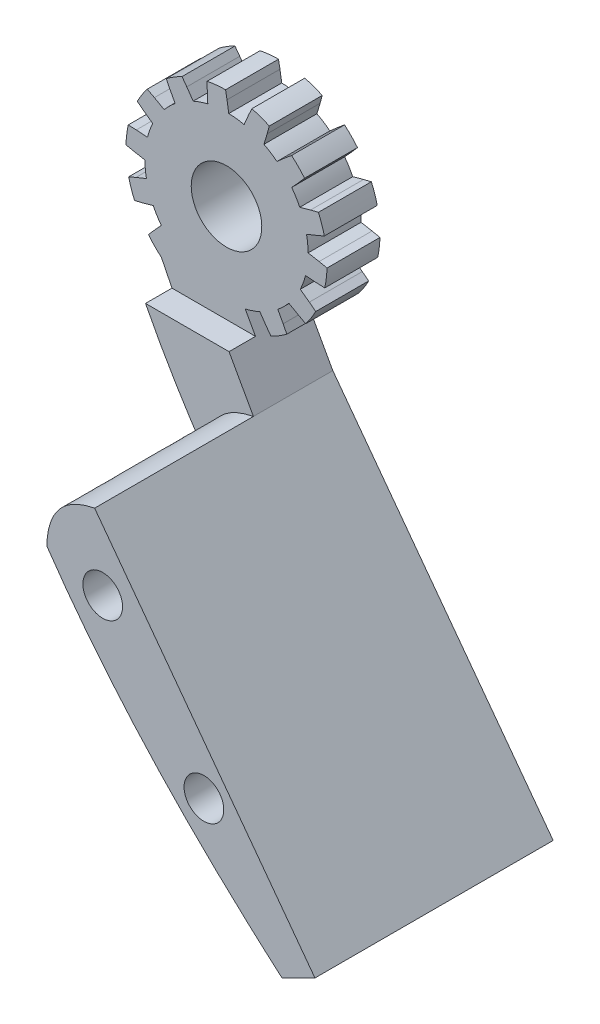
SolidWorks part; units mm, degrees
ref_plane "Front Plane" through (0, 0, 0) normal (0, 0, 1) x (1, 0, 0)
ref_plane "Top Plane" through (0, 0, 0) normal (0, 1, 0) x (1, 0, 0)
ref_plane "Right Plane" through (0, 0, 0) normal (1, 0, 0) x (0, 0, -1)
sketch "Sketch2" plane through (0, 0, 0) normal (0, 0, 1) x (1, 0, 0)
  line L595 (17.593, 3.4479) -> (18.4327, 3.8121)
  line L596 (16.415, 2.9762) -> (17.593, 3.4479)
  line L597 (15.6491, 5.2416) -> (16.8717, 5.5815)
  line L598 (16.8717, 5.5815) -> (17.7601, 5.8015)
  line L599 (5.2228, 10.175) -> (5.1635, 11.4426)
  line L600 (5.1635, 11.4426) -> (5.1467, 12.3577)
  line L601 (11.588, 9.3895) -> (11.9537, 10.6047)
  line L602 (11.9537, 10.6047) -> (12.1925, 11.4882)
  line L603 (9.3394, 10.2032) -> (9.8359, 11.371)
  line L604 (9.8359, 11.371) -> (10.2178, 12.2028)
  line L605 (14.7334, 6.7337) -> (15.5901, 7.6699)
  line L606 (15.5901, 7.6699) -> (16.1886, 8.3623)
  line L607 (13.0605, 8.4425) -> (14.0145, 9.2792)
  line L608 (14.0145, 9.2792) -> (14.7195, 9.8629)
  line L609 (-1.907, 1.1079) -> (-3.156, 1.3322)
  line L610 (-3.156, 1.3322) -> (-4.0519, 1.5194)
  line L611 (0.2752, 7.1388) -> (-0.8281, 7.7657)
  line L612 (-0.8281, 7.7657) -> (-1.6364, 8.1951)
  line L613 (-1.0184, 5.1275) -> (-2.0464, 5.8715)
  line L614 (-2.0464, 5.8715) -> (-2.7724, 6.4289)
  line L615 (3.5643, 9.6143) -> (2.8423, 10.6578)
  line L616 (2.8423, 10.6578) -> (2.3004, 11.3954)
  line L617 (1.5262, 8.3635) -> (0.9228, 9.4798)
  line L618 (0.9228, 9.4798) -> (0.5105, 10.297)
  line L619 (7.6018, 10.4176) -> (7.4041, 11.6711)
  line L620 (7.4041, 11.6711) -> (7.2358, 12.5707)
  line L621 (-0.0478, -4.3913) -> (-0.9045, -5.3274)
  line L622 (-0.9045, -5.3274) -> (-1.503, -6.0199)
  line L623 (1.6251, -6.1) -> (0.6711, -6.9367)
  line L624 (0.6711, -6.9367) -> (-0.0339, -7.5204)
  line L625 (-1.7294, -0.6337) -> (-2.9074, -1.1055)
  line L626 (-2.9074, -1.1055) -> (-3.7471, -1.4697)
  line L627 (-0.9635, -2.8991) -> (-2.1861, -3.239)
  line L628 (-2.1861, -3.239) -> (-3.0745, -3.459)
  line L629 (-1.6141, 3.4813) -> (-2.8801, 3.5674)
  line L630 (-2.8801, 3.5674) -> (-3.7947, 3.6036)
  line L631 (13.1594, -6.0211) -> (13.7628, -7.1374)
  line L632 (13.7628, -7.1374) -> (14.1751, -7.9546)
  line L633 (7.0838, -8.0751) -> (7.2815, -9.3286)
  line L634 (7.2815, -9.3286) -> (7.4497, -10.2283)
  line L635 (9.4628, -7.8326) -> (9.5221, -9.1001)
  line L636 (9.5221, -9.1001) -> (9.5389, -10.0152)
  line L637 (3.0976, -7.0471) -> (2.7319, -8.2622)
  line L638 (2.7319, -8.2622) -> (2.4931, -9.1458)
  line L639 (5.3462, -7.8607) -> (4.8497, -9.0285)
  line L640 (4.8497, -9.0285) -> (4.4678, -9.8603)
  line L641 (16.2997, -1.1388) -> (17.5657, -1.2249)
  line L642 (17.5657, -1.2249) -> (18.4803, -1.2611)
  line L643 (16.5926, 1.2345) -> (17.8416, 1.0103)
  line L644 (17.8416, 1.0103) -> (18.7375, 0.8231)
  line L645 (14.4104, -4.7963) -> (15.5137, -5.4232)
  line L646 (15.5137, -5.4232) -> (16.322, -5.8526)
  line L647 (15.704, -2.7851) -> (16.732, -3.529)
  line L648 (16.732, -3.529) -> (17.458, -4.0864)
  line L649 (11.1213, -7.2719) -> (11.8433, -8.3154)
  line L650 (11.8433, -8.3154) -> (12.3852, -9.053)
  arc A45 (12.3852, -9.053) -> (14.1751, -7.9546) centre (7.3428, 1.1712) ccw
  arc A46 (7.4497, -10.2283) -> (9.5389, -10.0152) centre (7.3428, 1.1712) ccw
  arc A48 (2.4931, -9.1458) -> (4.4678, -9.8603) centre (7.3428, 1.1712) ccw
  arc A50 (-1.503, -6.0199) -> (-0.0339, -7.5204) centre (7.3428, 1.1712) ccw
  arc A51 (5.3462, -7.8607) -> (7.0838, -8.0751) centre (7.3428, 1.1712) ccw
  arc A52 (-3.7471, -1.4697) -> (-3.0745, -3.459) centre (7.3428, 1.1712) ccw
  arc A53 (-3.7947, 3.6036) -> (-4.0519, 1.5194) centre (7.3428, 1.1712) ccw
  arc A54 (-1.6364, 8.1951) -> (-2.7724, 6.4289) centre (7.3428, 1.1712) ccw
  arc A55 (2.3004, 11.3954) -> (0.5105, 10.297) centre (7.3428, 1.1712) ccw
  arc A56 (7.2358, 12.5707) -> (5.1467, 12.3577) centre (7.3428, 1.1712) ccw
  arc A57 (12.1925, 11.4882) -> (10.2178, 12.2028) centre (7.3428, 1.1712) ccw
  arc A58 (16.1886, 8.3623) -> (14.7195, 9.8629) centre (7.3428, 1.1712) ccw
  arc A59 (18.4327, 3.8121) -> (17.7601, 5.8015) centre (7.3428, 1.1712) ccw
  arc A60 (18.4803, -1.2611) -> (18.7375, 0.8231) centre (7.3428, 1.1712) ccw
  arc A61 (16.322, -5.8526) -> (17.458, -4.0864) centre (7.3428, 1.1712) ccw
  arc A62 (1.6251, -6.1) -> (3.0976, -7.0471) centre (7.3428, 1.1712) ccw
  arc A63 (-0.9635, -2.8991) -> (-0.0478, -4.3913) centre (7.3428, 1.1712) ccw
  arc A64 (-1.907, 1.1079) -> (-1.7294, -0.6337) centre (7.3428, 1.1712) ccw
  arc A65 (-1.0184, 5.1275) -> (-1.6141, 3.4813) centre (7.3428, 1.1712) ccw
  arc A66 (1.5262, 8.3635) -> (0.2752, 7.1388) centre (7.3428, 1.1712) ccw
  arc A67 (5.2228, 10.175) -> (3.5643, 9.6143) centre (7.3428, 1.1712) ccw
  arc A68 (9.3394, 10.2032) -> (7.6018, 10.4176) centre (7.3428, 1.1712) ccw
  arc A69 (13.0605, 8.4425) -> (11.588, 9.3895) centre (7.3428, 1.1712) ccw
  arc A70 (15.6491, 5.2416) -> (14.7334, 6.7337) centre (7.3428, 1.1712) ccw
  arc A71 (16.5926, 1.2345) -> (16.415, 2.9762) centre (7.3428, 1.1712) ccw
  arc A72 (15.704, -2.7851) -> (16.2997, -1.1388) centre (7.3428, 1.1712) ccw
  arc A73 (13.1594, -6.0211) -> (14.4104, -4.7963) centre (7.3428, 1.1712) ccw
  arc A74 (9.4628, -7.8326) -> (11.1213, -7.2719) centre (7.3428, 1.1712) ccw
extrude "Boss-Extrude1" add sketch "Sketch2" against normal blind 7 and the other way blind 2
sketch "Sketch5" plane through (0, 0, 2) normal (0, 0, 1) x (1, 0, 0)
  line L1 (11.4711, 11.5) -> (18.1778, 11.5) construction
  line L2 (-0.0339, -7.5204) -> (0.6711, -6.9367) construction
  line L6 (34.628, -50.4079) -> (38.3692, -48.5518)
  line L7 (-0.0339, -7.5204) -> (0.8657, -2.8432)
  line L8 (38.3692, -48.5518) -> (13.394, -14.9204)
  line L9 (0.8657, -2.8432) -> (9.4628, -7.8326)
  arc A1 (9.4628, -7.8326) -> (11.1213, -7.2719) centre (7.3428, 1.1712) ccw construction
  arc A2 (-1.503, -6.0199) -> (-0.0339, -7.5204) centre (7.3428, 1.1712) ccw construction
  spline S0 degree 1 poles (13.394, -14.9204) (9.4628, -7.8326) knots 0 0 1 1
  spline S1 degree 3 poles (34.628, -50.4079) (20.7375, -38.3435) (7.9572, -24.2645) (-0.0339, -7.5204) knots 0 0 0 0 1 1 1 1
  point P2 (13.7656, -15.5368)
  point P7 (36.9272, -50.3448)
  point P15 (0, 0)
  point P21 (38.3692, -48.5518)
  point P22 (13.394, -14.9204)
  point P23 (34.628, -50.4079)
  point P24 (18.5457, -34.6849)
  point P25 (6.0579, -18.4446)
  point P26 (0, -7.5204)
extrude "Boss-Extrude3" add sketch "Sketch5" against normal up to surface (9 mm away) up to face at (7.3428, 1.1712, -7)
sketch "Sketch6" plane through (0, 0, -7) normal (0, 0, -1) x (-1, 0, 0)
  circle A2 centre (-7.3428, 1.1712) radius 4
  point P1 (0, 0)
  dimension "D1" = 8
extrude "Cut-Extrude1" cut sketch "Sketch6" against normal blind 18
sketch "Sketch7" plane through (0, 0, 2) normal (0, 0, 1) x (1, 0, 0)
  line L49 (34.628, -50.4079) -> (38.3692, -48.5518)
  line L50 (38.3692, -48.5518) -> (13.394, -14.9204)
  line L51 (13.394, -14.9204) -> (9.4628, -7.8326)
  line L52 (11.1213, -7.2719) -> (11.8433, -8.3154)
  line L53 (11.8433, -8.3154) -> (12.3852, -9.053)
  line L54 (14.1751, -7.9546) -> (13.7628, -7.1374)
  line L55 (13.7628, -7.1374) -> (13.1594, -6.0211)
  line L56 (14.4104, -4.7963) -> (15.5137, -5.4232)
  line L57 (15.5137, -5.4232) -> (16.322, -5.8526)
  line L58 (17.458, -4.0864) -> (16.732, -3.529)
  line L59 (16.732, -3.529) -> (15.704, -2.7851)
  line L60 (16.2997, -1.1388) -> (17.5657, -1.2249)
  line L61 (17.5657, -1.2249) -> (18.4803, -1.2611)
  line L62 (18.7375, 0.8231) -> (17.8416, 1.0103)
  line L63 (17.8416, 1.0103) -> (16.5926, 1.2345)
  line L64 (16.415, 2.9762) -> (17.593, 3.4479)
  line L65 (17.593, 3.4479) -> (18.4327, 3.8121)
  line L66 (17.7601, 5.8015) -> (16.8717, 5.5815)
  line L67 (16.8717, 5.5815) -> (15.6491, 5.2416)
  line L68 (14.7334, 6.7337) -> (15.5901, 7.6699)
  line L69 (15.5901, 7.6699) -> (16.1886, 8.3623)
  line L70 (14.7195, 9.8629) -> (14.0145, 9.2792)
  line L71 (14.0145, 9.2792) -> (13.0605, 8.4425)
  line L72 (11.588, 9.3895) -> (11.9537, 10.6047)
  line L73 (11.9537, 10.6047) -> (12.1925, 11.4882)
  line L74 (10.2178, 12.2028) -> (9.8359, 11.371)
  line L75 (9.8359, 11.371) -> (9.3394, 10.2032)
  line L76 (7.6018, 10.4176) -> (7.4041, 11.6711)
  line L77 (7.4041, 11.6711) -> (7.2358, 12.5707)
  line L78 (5.1467, 12.3577) -> (5.1635, 11.4426)
  line L79 (5.1635, 11.4426) -> (5.2228, 10.175)
  line L80 (3.5643, 9.6143) -> (2.8423, 10.6578)
  line L81 (2.8423, 10.6578) -> (2.3004, 11.3954)
  line L82 (0.5105, 10.297) -> (0.9228, 9.4798)
  line L83 (0.9228, 9.4798) -> (1.5262, 8.3635)
  line L84 (0.2752, 7.1388) -> (-0.8281, 7.7657)
  line L85 (-0.8281, 7.7657) -> (-1.6364, 8.1951)
  line L86 (-2.7724, 6.4289) -> (-2.0464, 5.8715)
  line L87 (-2.0464, 5.8715) -> (-1.0184, 5.1275)
  line L88 (-1.6141, 3.4813) -> (-2.8801, 3.5674)
  line L89 (-2.8801, 3.5674) -> (-3.7947, 3.6036)
  line L90 (-4.0519, 1.5194) -> (-3.156, 1.3322)
  line L91 (-3.156, 1.3322) -> (-1.907, 1.1079)
  line L92 (-1.7294, -0.6337) -> (-2.9074, -1.1055)
  line L93 (-2.9074, -1.1055) -> (-3.7471, -1.4697)
  line L94 (-3.0745, -3.459) -> (-2.1861, -3.239)
  line L95 (-2.1861, -3.239) -> (-0.9635, -2.8991)
  line L96 (-0.0478, -4.3913) -> (-0.9045, -5.3274)
  line L97 (-0.9045, -5.3274) -> (-1.503, -6.0199)
  line L98 (34.628, -50.4079) -> (38.3692, -48.5518)
  line L99 (38.3692, -48.5518) -> (13.394, -14.9204)
  arc A24 (-1.503, -6.0199) -> (-0.0339, -7.5204) centre (7.3428, 1.1712) ccw
  arc A25 (9.4628, -7.8326) -> (11.1213, -7.2719) centre (7.3428, 1.1712) ccw
  arc A26 (12.3852, -9.053) -> (14.1751, -7.9546) centre (7.3428, 1.1712) ccw
  arc A27 (13.1594, -6.0211) -> (14.4104, -4.7963) centre (7.3428, 1.1712) ccw
  arc A28 (16.322, -5.8526) -> (17.458, -4.0864) centre (7.3428, 1.1712) ccw
  arc A29 (15.704, -2.7851) -> (16.2997, -1.1388) centre (7.3428, 1.1712) ccw
  arc A30 (18.4803, -1.2611) -> (18.7375, 0.8231) centre (7.3428, 1.1712) ccw
  arc A31 (16.5926, 1.2345) -> (16.415, 2.9762) centre (7.3428, 1.1712) ccw
  arc A32 (18.4327, 3.8121) -> (17.7601, 5.8015) centre (7.3428, 1.1712) ccw
  arc A33 (15.6491, 5.2416) -> (14.7334, 6.7337) centre (7.3428, 1.1712) ccw
  arc A34 (16.1886, 8.3623) -> (14.7195, 9.8629) centre (7.3428, 1.1712) ccw
  arc A35 (13.0605, 8.4425) -> (11.588, 9.3895) centre (7.3428, 1.1712) ccw
  arc A36 (12.1925, 11.4882) -> (10.2178, 12.2028) centre (7.3428, 1.1712) ccw
  arc A37 (9.3394, 10.2032) -> (7.6018, 10.4176) centre (7.3428, 1.1712) ccw
  arc A38 (7.2358, 12.5707) -> (5.1467, 12.3577) centre (7.3428, 1.1712) ccw
  arc A39 (5.2228, 10.175) -> (3.5643, 9.6143) centre (7.3428, 1.1712) ccw
  arc A40 (2.3004, 11.3954) -> (0.5105, 10.297) centre (7.3428, 1.1712) ccw
  arc A41 (1.5262, 8.3635) -> (0.2752, 7.1388) centre (7.3428, 1.1712) ccw
  arc A42 (-1.6364, 8.1951) -> (-2.7724, 6.4289) centre (7.3428, 1.1712) ccw
  arc A43 (-1.0184, 5.1275) -> (-1.6141, 3.4813) centre (7.3428, 1.1712) ccw
  arc A44 (-3.7947, 3.6036) -> (-4.0519, 1.5194) centre (7.3428, 1.1712) ccw
  arc A45 (-1.907, 1.1079) -> (-1.7294, -0.6337) centre (7.3428, 1.1712) ccw
  arc A46 (-3.7471, -1.4697) -> (-3.0745, -3.459) centre (7.3428, 1.1712) ccw
  arc A47 (-0.9635, -2.8991) -> (-0.0478, -4.3913) centre (7.3428, 1.1712) ccw
  spline S0 degree 2 poles (7.978, -21.3451) (8.1121, -15.9213) (13.394, -14.9204) knots 0 0 0 1 1 1
  spline S1 degree 3 poles (2689.3147, 1264.9891) (-3237.4149, -692.61) (3465.2731, 248.2767) (-2933.8872, -462.9976) knots -8.084515 -8.084515 -8.084515 -8.084515 11.039067 11.039067 11.039067 11.039067 only from (-0.0339, -7.5204) to (34.628, -50.4079)
  spline S2 degree 3 poles (7.978, -21.3451) (15.4138, -32.2101) (24.7396, -41.8194) (34.628, -50.4079) knots 0.288119 0.288119 0.288119 0.288119 1 1 1 1
  dimension "D1" = 0
extrude "Boss-Extrude4" add sketch "Sketch7" along normal blind 18
sketch "Sketch8" plane through (0, 0, -7) normal (0, 0, -1) x (-1, 0, 0)
  circle A2 centre (-14.3128, -23.0208) radius 2.25
  circle A3 centre (-25.7856, -37.2154) radius 2.25
extrude "Cut-Extrude2" cut sketch "Sketch8" against normal through all
sketch "Sketch9" plane through (0, 0, 0) normal (1, 0, 0) x (0, 0, -1)
  line L0 (7, 3.8121) -> (7, 5.8015) construction
  line L1 (-9.3233, 17.5423) -> (1, 17.5423)
  line L2 (-9.3233, 17.5423) -> (-9.3233, -9.939)
  line L3 (-9.3233, -9.939) -> (1, -9.939)
  line L4 (1, 17.5423) -> (1, -9.939)
  dimension "D1" = 6
extrude "Cut-Extrude3" cut sketch "Sketch9" along normal through all and the other way through all
